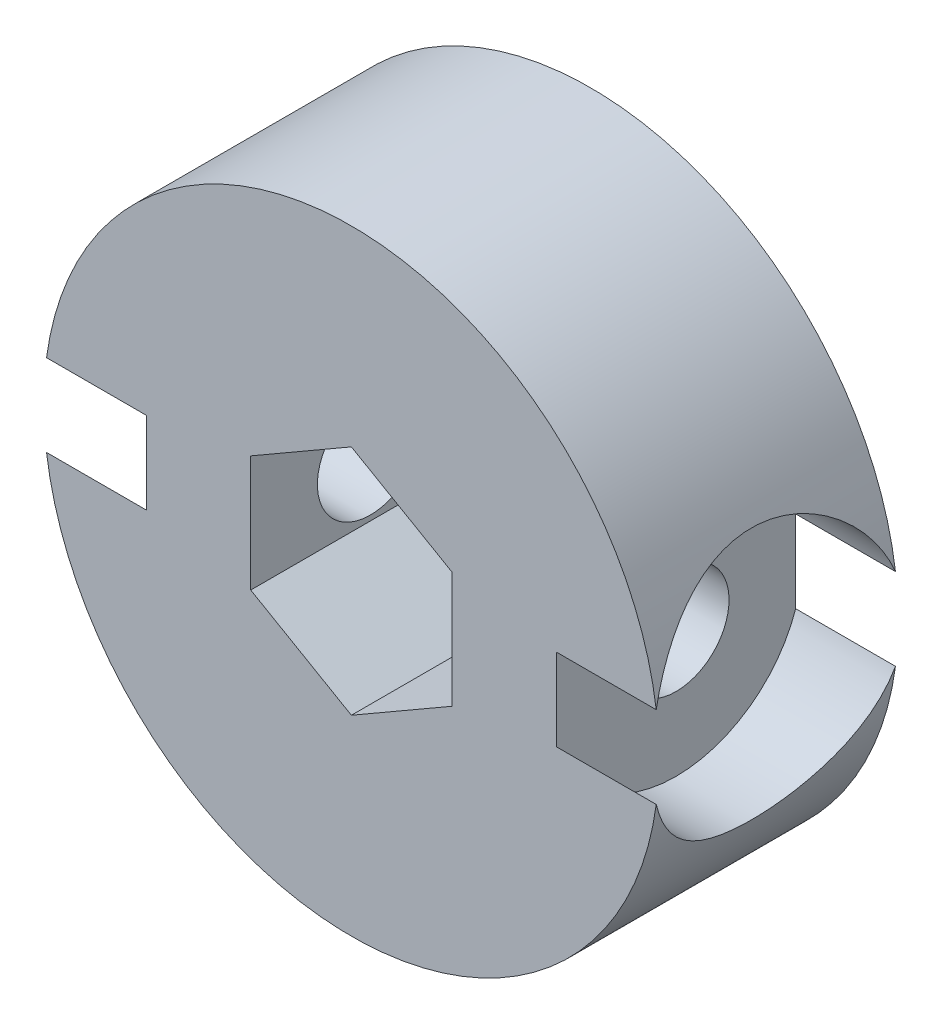
SolidWorks part; units mm, degrees
ref_plane "Front Plane" through (0, 0, 0) normal (0, 0, 1) x (1, 0, 0)
ref_plane "Top Plane" through (0, 0, 0) normal (0, 1, 0) x (1, 0, 0)
ref_plane "Right Plane" through (0, 0, 0) normal (1, 0, 0) x (0, 0, -1)
sketch "Sketch1" plane through (0, 0, 0) normal (0, 0, 1) x (1, 0, 0)
  line L0 (0, -3.4) -> (0, 3.4) construction
  line L1 (-2.9445, -1.7) -> (2.9445, 1.7) construction
  line L2 (-2.9445, 1.7) -> (2.9445, -1.7) construction
  line L3 (0, 3.4) -> (2.9445, 1.7)
  line L4 (2.9445, 1.7) -> (2.9445, -1.7)
  line L5 (2.9445, -1.7) -> (0, -3.4)
  line L6 (0, -3.4) -> (-2.9445, -1.7)
  line L7 (-2.9445, -1.7) -> (-2.9445, 1.7)
  line L8 (-2.9445, 1.7) -> (0, 3.4)
  circle A0 centre (0, 0) radius 9
  circle A2 centre (0, 0) radius 3.4 construction
  point P7 (0, 0)
  point P9 (0, 0)
  point P13 (0, 0)
  point P14 (0, 0)
extrude "Boss-Extrude1" add sketch "Sketch1" along normal blind 7
ref_plane "Plane1" through (0, 0, 0) normal (-1, 0, 0) x (0, 0, 1)
sketch "Sketch5" plane through (0, 0, 0) normal (-1, 0, 0) x (0, 0, 1)
  line L0 (7, -9) -> (7, 9) construction
  line L1 (7, 0) -> (3.5, 0) construction
  circle A0 centre (3.5, 0) radius 1.55
  point P10 (7, 0)
extrude "Cut-Extrude1" cut sketch "Sketch5" against normal blind 9 and the other way blind 9
ref_plane "Plane2" through (-6, 0, 0) normal (-1, 0, 0) x (0, 0, 1)
ref_plane "Plane3" through (6, 0, 0) normal (-1, 0, 0) x (0, 0, 1)
sketch "Sketch6" plane through (-6, 0, 0) normal (-1, 0, 0) x (0, 0, 1)
  circle A0 centre (3.5, 0) radius 3.7
extrude "Cut-Extrude2" cut sketch "Sketch6" along normal blind 5.5
sketch "Sketch7" plane through (6, 0, 0) normal (-1, 0, 0) x (0, 0, 1)
  circle A0 centre (3.5, 0) radius 3.7
extrude "Cut-Extrude3" cut sketch "Sketch7" against normal blind 5.5 contours A0
